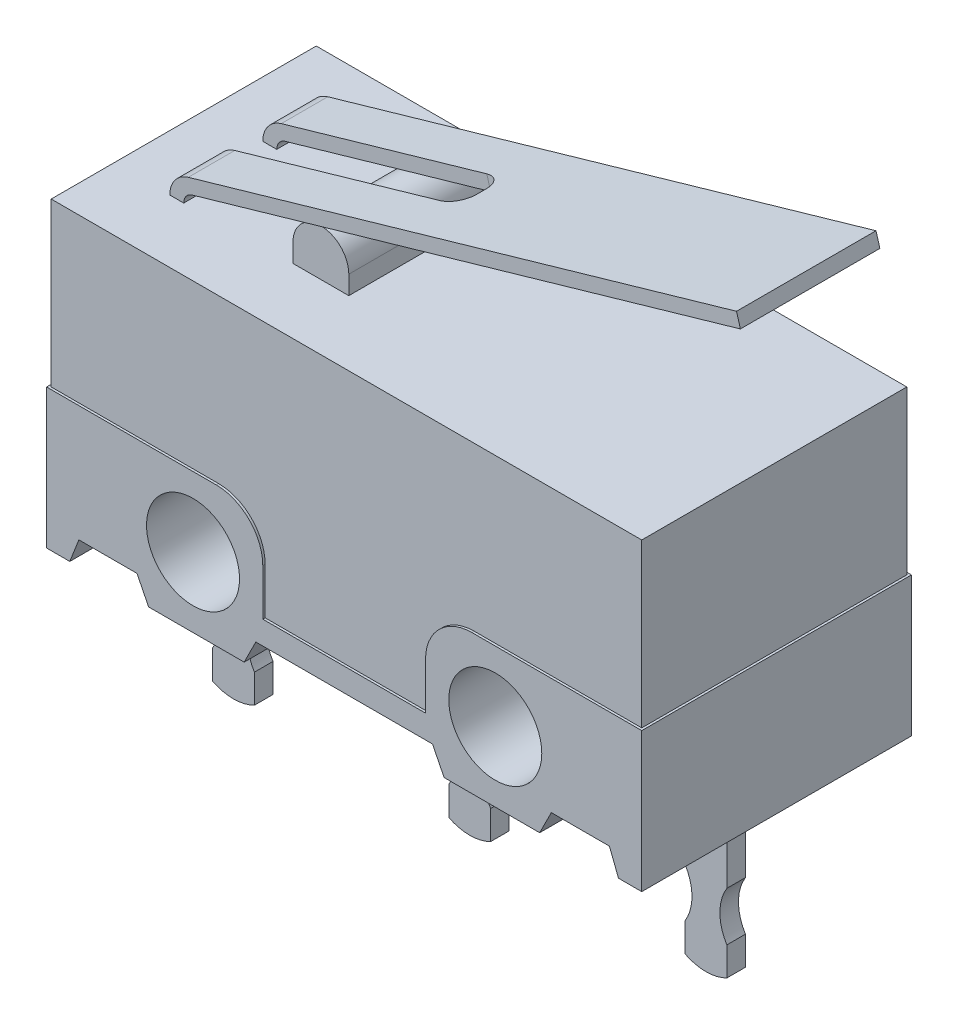
SolidWorks part; units mm, degrees
ref_plane "Front Plane" through (0, 0, 0) normal (0, 0, 1) x (1, 0, 0)
ref_plane "Top Plane" through (0, 0, 0) normal (0, 1, 0) x (1, 0, 0)
ref_plane "Right Plane" through (0, 0, 0) normal (1, 0, 0) x (0, 0, -1)
sketch "Sketch1" plane through (0, 0, 0) normal (0, 0, 1) x (1, 0, 0)
  line L0 (0, 0) -> (-3.25, 0) construction
  line L1 (0, 0) -> (3.25, 0) construction
  line L5 (6.4, -1.5) -> (-6.4, -1.5)
  line L6 (-6.4, -1.5) -> (-6.4, 1.5)
  line L7 (-6.4, 1.5) -> (-2.75, 1.5)
  line L8 (-1.75, 0.5) -> (-1.75, -0.5)
  line L9 (-1.75, -0.5) -> (1.75, -0.5)
  line L10 (1.75, -0.5) -> (1.75, 0.5)
  line L11 (2.75, 1.5) -> (6.4, 1.5)
  line L12 (6.4, 1.5) -> (6.4, -1.5)
  circle A0 centre (-3.25, 0) radius 1
  circle A1 centre (3.25, 0) radius 1
  arc A2 (-1.75, 0.5) -> (-2.75, 1.5) centre (-2.75, 0.5) ccw
  arc A3 (2.75, 1.5) -> (1.75, 0.5) centre (2.75, 0.5) ccw
  dimension "D1" = 2
  dimension "D7" = 1
  dimension "D8" = 1
  dimension "D2" = 6.5
  dimension "D3" = 1.5
  dimension "D4" = 1.5
  dimension "D5" = 1.5
  dimension "D6" = 1.5
  dimension "D9" = 3.15
  dimension "D10" = 3.15
  dimension "D11" = 1
extrude "Boss-Extrude1" add sketch "Sketch1" along normal mid plane 5.8
sketch "Sketch3" plane through (0, 0, 2.9) normal (0, 0, 1) x (1, 0, 0)
  line L0 (-3.25, 0) -> (-3.25, 5) construction
  line L1 (3.25, 0) -> (3.25, 5) construction
  line L2 (-3.25, 5) -> (-6.35, 5)
  line L3 (-6.35, 5) -> (-6.35, 1.5)
  line L4 (-2.75, 1.5) -> (-6.4, 1.5) construction
  line L5 (-3.25, 5) -> (3.25, 5)
  line L6 (3.25, 5) -> (6.35, 5)
  line L7 (6.35, 5) -> (6.35, 1.5)
  line L13 (-6.4, 1.5) -> (-6.4, -1.5)
  line L14 (-6.4, -1.5) -> (6.4, -1.5)
  line L15 (6.4, -1.5) -> (6.4, 1.5)
  line L16 (6.4, 1.5) -> (2.75, 1.5)
  line L17 (1.75, 0.5) -> (1.75, -0.5)
  line L18 (1.75, -0.5) -> (-1.75, -0.5)
  line L19 (-1.75, -0.5) -> (-1.75, 0.5)
  line L20 (-2.75, 1.5) -> (-6.4, 1.5)
  line L24 (6.35, 1.5) -> (2.75, 1.5)
  line L25 (1.75, 0.5) -> (1.75, -0.5)
  line L26 (1.75, -0.5) -> (-1.75, -0.5)
  line L27 (-1.75, -0.5) -> (-1.75, 0.5)
  line L28 (-2.75, 1.5) -> (-6.35, 1.5)
  arc A2 (2.75, 1.5) -> (1.75, 0.5) centre (2.75, 0.5) ccw
  arc A3 (-1.75, 0.5) -> (-2.75, 1.5) centre (-2.75, 0.5) ccw
  arc A4 (2.75, 1.5) -> (1.75, 0.5) centre (2.75, 0.5) ccw
  arc A5 (-1.75, 0.5) -> (-2.75, 1.5) centre (-2.75, 0.5) ccw
  dimension "D1" = 5
  dimension "D2" = 0
  dimension "D3" = 12.7
extrude "Boss-Extrude2" add sketch "Sketch3" along normal mid plane 5.7 from surface at -2.9 separate body starting at plane "Front Plane"
sketch "Sketch4" plane through (0, 0, 2.9) normal (0, 0, 1) x (1, 0, 0)
  line L0 (-5.9, -1.5) -> (-5.705, -1)
  line L1 (-6.4, -1.5) -> (6.4, -1.5) construction
  line L2 (-5.705, -1) -> (-4.455, -1)
  line L3 (-4.455, -1) -> (-4.205, -1.5)
  line L4 (-2.15, -1.5) -> (-1.9, -1)
  line L5 (-1.9, -1) -> (1.9, -1)
  line L6 (0, -1.5) -> (0, -1) construction
  line L7 (-3.25, 0) -> (-3.25, -1.5) construction
  line L8 (-5.9, -1.5) -> (-4.205, -1.5)
  line L9 (-2.15, -1.5) -> (2.15, -1.5)
  line L10 (-5.08, -1) -> (-5.08, -1.5) construction
  line L11 (2.15, -1.5) -> (1.9, -1)
  line L12 (5.9, -1.5) -> (4.205, -1.5)
  line L13 (5.9, -1.5) -> (5.705, -1)
  line L14 (5.705, -1) -> (4.455, -1)
  line L15 (4.455, -1) -> (4.205, -1.5)
  point P18 (0, 0)
  dimension "D1" = 0.5
  dimension "D2" = 0.5
  dimension "D3" = 5.08
  dimension "D4" = 1.1
  dimension "D5" = 0.15
  dimension "D6" = 1.25
  dimension "D7" = 0.25
extrude "Cut-Extrude1" cut sketch "Sketch4" against normal through all
sketch "Sketch5" plane through (0, 0, 0) normal (0, 0, 1) x (1, 0, 0)
  line L0 (-5.08, -1) -> (-5.08, -5) construction
  line L1 (-4.455, -1) -> (-5.705, -1) construction
  line L2 (0, -1) -> (0, -5) construction
  line L3 (1.9, -1) -> (-1.9, -1) construction
  line L4 (-5.53, -1) -> (-5.53, -3.2232)
  line L5 (-5.08, -3.75) -> (-4.78, -3.75) construction
  line L6 (-4.63, -1) -> (-4.63, -3.2232)
  line L7 (-5.38, -3.75) -> (-5.08, -3.75) construction
  line L8 (-4.63, -1) -> (-4.63, -5) construction
  line L9 (-5.53, -1) -> (-5.53, -5) construction
  line L10 (-5.53, -4.2768) -> (-5.53, -4.893)
  line L11 (-4.63, -4.2768) -> (-4.63, -4.893)
  line L12 (0, -1) -> (-5.08, -1) construction
  line L13 (-2.54, -1) -> (-2.54, -2.6112) construction
  line L14 (-5.08, -1) -> (-5.53, -1)
  line L15 (-5.08, -1) -> (-4.63, -1)
  line L16 (-0.45, -4.2768) -> (-0.45, -4.893)
  line L17 (0.45, -4.2768) -> (0.45, -4.893)
  line L18 (-0.45, -1) -> (-0.45, -3.2232)
  line L19 (0.45, -1) -> (0.45, -3.2232)
  line L20 (0, -1) -> (0.45, -1)
  line L21 (0, -1) -> (-0.45, -1)
  line L22 (5.53, -4.2768) -> (5.53, -4.893)
  line L23 (4.63, -4.2768) -> (4.63, -4.893)
  line L24 (5.53, -1) -> (5.53, -3.2232)
  line L25 (4.63, -1) -> (4.63, -3.2232)
  line L26 (5.08, -1) -> (5.53, -1)
  line L27 (5.08, -1) -> (4.63, -1)
  arc A0 (-5.53, -4.893) -> (-4.63, -4.893) centre (-5.08, -4) ccw
  arc A1 (-5.53, -4.2768) -> (-5.53, -3.2232) centre (-6.38, -3.75) ccw
  arc A2 (-4.63, -3.2232) -> (-4.63, -4.2768) centre (-3.78, -3.75) ccw
  arc A3 (0.45, -4.893) -> (-0.45, -4.893) centre (0, -4) cw
  arc A4 (0.45, -4.2768) -> (0.45, -3.2232) centre (1.3, -3.75) cw
  arc A5 (-0.45, -3.2232) -> (-0.45, -4.2768) centre (-1.3, -3.75) cw
  arc A6 (5.53, -4.893) -> (4.63, -4.893) centre (5.08, -4) cw
  arc A7 (4.63, -3.2232) -> (4.63, -4.2768) centre (3.78, -3.75) cw
  arc A8 (5.53, -4.2768) -> (5.53, -3.2232) centre (6.38, -3.75) cw
  dimension "D4" = 2
  dimension "D5" = 2
  dimension "D1" = 3.5
  dimension "D6" = 0.3
  dimension "D7" = 1.25
  dimension "D2" = 0.45
  dimension "D3" = 0.45
extrude "Boss-Extrude3" add sketch "Sketch5" along normal mid plane 0.4 separate body
sketch "Sketch6" plane through (0, 0, 2.85) normal (0, 0, 1) x (1, 0, 0)
  line L0 (3.25, 0) -> (3.25, 5) construction
  line L1 (6.35, 5) -> (-6.35, 5) construction
  line L2 (6.35, 5) -> (-6.35, 5) construction
  line L3 (-1.35, 5) -> (-2.55, 5)
  line L4 (-2.55, 5.4) -> (-2.55, 5)
  line L5 (-1.35, 5.4) -> (-1.35, 5)
  line L6 (-1.95, 5.4) -> (-1.95, 6) construction
  arc A0 (-1.35, 5.4) -> (-2.55, 5.4) centre (-1.95, 5.4) ccw
  point P7 (-1.95, 5)
  dimension "D1" = 5.2
  dimension "D2" = 1.2
  dimension "D3" = 6
extrude "Boss-Extrude4" add sketch "Sketch6" along normal mid plane 2.9 from surface at -2.85 separate body starting at plane "Front Plane"
sketch "Sketch7" plane through (0, 0, 2.85) normal (0, 0, 1) x (1, 0, 0)
  line L0 (6.35, 5) -> (-6.35, 5) construction
  line L1 (-4.6693, 5.2402) -> (7.1213, 8.6406)
  line L2 (-6.35, 5) -> (-4.85, 5) construction
  line L3 (-4.7524, 5.5285) -> (7.0382, 8.9289)
  line L4 (7.0382, 8.9289) -> (7.1213, 8.6406)
  line L5 (-5.15, 5) -> (-4.85, 5)
  arc A0 (-1.35, 5.4) -> (-2.55, 5.4) centre (-1.95, 5.4) ccw construction
  arc A1 (-1.35, 5.4) -> (-2.55, 5.4) centre (-1.95, 5.4) ccw construction
  arc A2 (-4.6693, 5.2402) -> (-4.85, 5) centre (-4.6, 5) ccw
  arc A3 (-4.7524, 5.5285) -> (-5.15, 5) centre (-4.6, 5) ccw
  dimension "D2" = 0.5
  dimension "D1" = 1.5
  dimension "D4" = 12.8
  dimension "D3" = 0.3
extrude "Boss-Extrude5" add sketch "Sketch7" along normal mid plane 3 from surface at -2.85 separate body starting at plane "Front Plane"
sketch "Sketch8" plane through (-1.8369, 6.3693, 0) normal (-0.2771, 0.9608, 0) x (0.9608, 0.2771, 0)
  line L0 (1.5657, 0.5) -> (-3.0343, 0.5)
  line L2 (-3.0343, -1.5) -> (-3.0343, 1.5) construction
  line L3 (-3.0343, -0.5) -> (1.5657, -0.5)
  line L4 (1.9657, -0.1) -> (1.9657, 0)
  line L5 (1.9657, 0) -> (1.9657, 0.1)
  line L6 (0, 0) -> (1.9657, 0) construction
  line L7 (-3.0343, 0.5) -> (-4.5343, 0.5)
  line L8 (-4.5343, 0.5) -> (-4.5343, -0.5)
  line L9 (-4.5343, -0.5) -> (-3.0343, -0.5)
  arc A0 (1.5657, -0.5) -> (1.9657, -0.1) centre (1.5657, -0.1) ccw
  arc A1 (1.5657, 0.5) -> (1.9657, 0.1) centre (1.5657, 0.1) cw
  point P15 (1.9657, 0.5)
  dimension "D3" = 0.4
  dimension "D1" = 0.5
  dimension "D2" = 1.5
  dimension "D4" = 5
extrude "Cut-Extrude2" cut sketch "Sketch8" against normal through all
